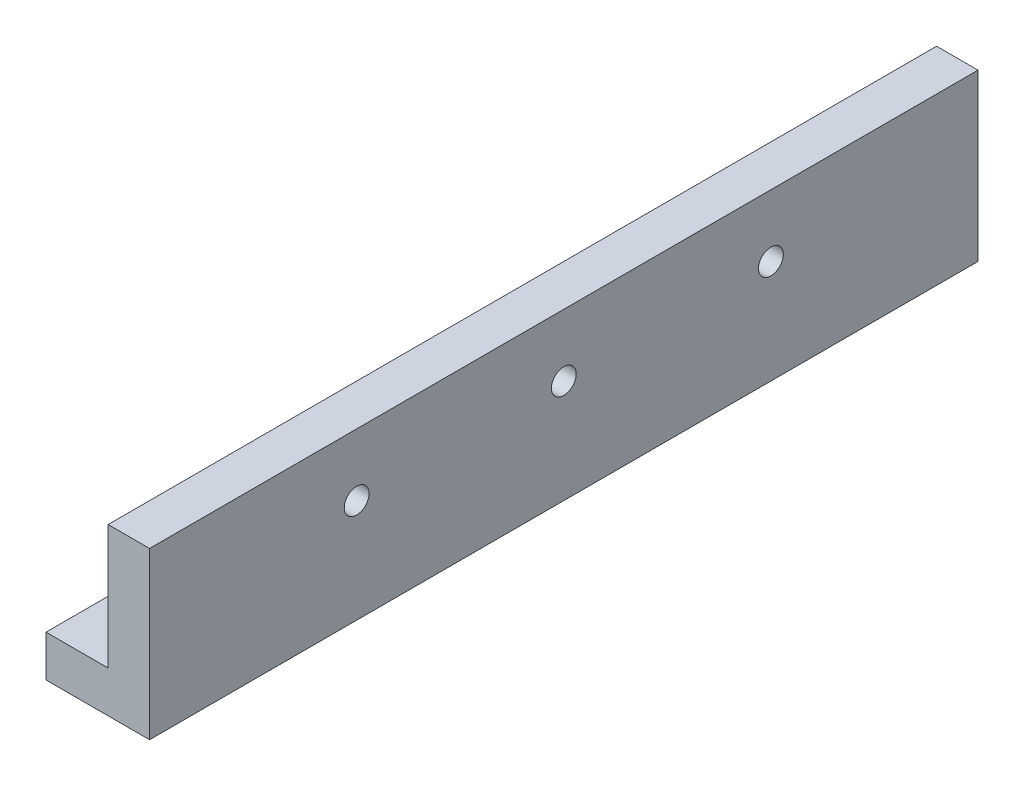
SolidWorks part; units mm, degrees
ref_plane "前基準面" through (0, 0, 0) normal (0, 0, 1) x (1, 0, 0)
ref_plane "上基準面" through (0, 0, 0) normal (0, 1, 0) x (1, 0, 0)
ref_plane "右基準面" through (0, 0, 0) normal (1, 0, 0) x (0, 0, -1)
sketch "草圖1" plane through (0, 0, 0) normal (0, 0, 1) x (1, 0, 0)
  line L0 (-5.3385, 191.7716) -> (-5.3385, 161.7716)
  line L2 (-5.3385, 161.7716) -> (-20.3385, 161.7716)
  line L3 (-20.3385, 161.7716) -> (-20.3385, 151.7716)
  line L4 (-20.3385, 151.7716) -> (4.6615, 151.7716)
  line L5 (4.6615, 151.7716) -> (4.6615, 191.7716)
  line L6 (4.6615, 191.7716) -> (-5.3385, 191.7716)
  point P2 (-20.3385, 151.7716)
  dimension "D1" = 15
  dimension "D2" = 10
  dimension "D3" = 30
  dimension "D4" = 10
extrude "填料-伸長1" add sketch "草圖1" against normal blind 200
sketch "草圖2" plane through (4.6615, 0, 0) normal (1, 0, 0) x (0, 0, -1)
  line L1 (200, 161.7716) -> (0, 161.7716) construction
  line L3 (200, 151.7716) -> (200, 191.7716) construction
  circle A2 centre (150, 176.7716) radius 3
  dimension "D1" = 15
  dimension "D3" = 6
  dimension "D7" = 50
extrude "除料-伸長1" cut sketch "草圖2" against normal up to surface (10 mm away) and the other way through all up to face at (-5.3385, 176.7716, -100)
pattern_linear "LPattern1" count 3 spacing 50 along (0, 0, 1) of "除料-伸長1"
